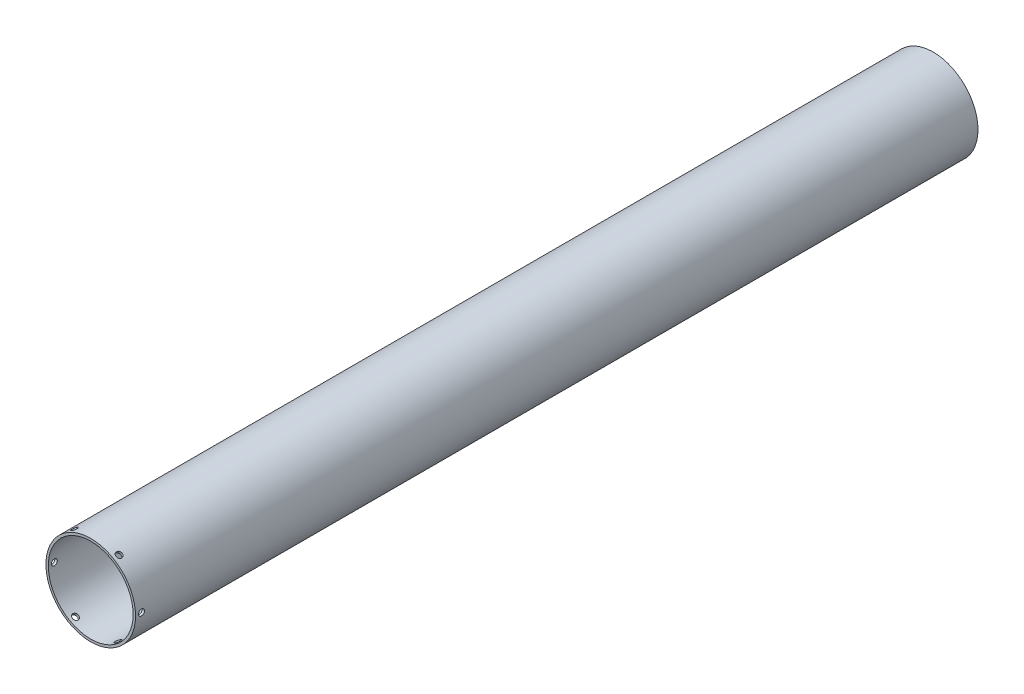
SolidWorks part; units mm, degrees
other "DetailItem1"
other "DetailItem2"
material "6063-O, Extruded Rod (SS)"
ref_plane "Front Plane" through (0, 0, 0) normal (0, 0, 1) x (1, 0, 0)
ref_plane "Top Plane" through (0, 0, 0) normal (0, 1, 0) x (1, 0, 0)
ref_plane "Right Plane" through (0, 0, 0) normal (1, 0, 0) x (0, 0, -1)
sketch "Sketch1" plane through (0, 0, 0) normal (0, 0, 1) x (1, 0, 0)
  circle A0 centre (0, 0) radius 35.5
  circle A1 centre (0, 0) radius 37.5
  dimension "D1" = 75
  dimension "D2" = 2
extrude "Boss-Extrude1" add sketch "Sketch1" along normal mid plane 705
ref_plane "Bolt to bulkhead" through (37.5, 0, 0) normal (1, 0, 0) x (0, 0, -1)
sketch "Sketch2" plane through (37.5, 0, 0) normal (1, 0, 0) x (0, 0, -1)
  line L0 (-352.5, 0) -> (-347.5, 0) construction
  line L1 (-352.5, 37.5) -> (-352.5, -37.5) construction
  circle A0 centre (-347.5, 0) radius 2.5
  dimension "D2" = 5
  dimension "D1" = 5
extrude "Cut-Extrude1" cut sketch "Sketch2" against normal up to surface (2 mm away) up to face at (35.5, 0, 352.5)
pattern_circular "CirPattern1" count 6 over 360 about axis through (0, 0, 352.5) along (0, 0, 1) of "Cut-Extrude1"
